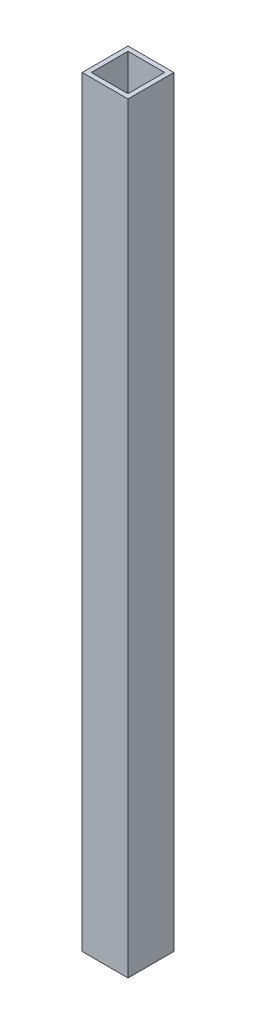
SolidWorks part; units mm, degrees
material "氧化铝"
ref_plane "前视基准面" through (0, 0, 0) normal (0, 0, 1) x (1, 0, 0)
ref_plane "上视基准面" through (0, 0, 0) normal (0, 1, 0) x (1, 0, 0)
ref_plane "右视基准面" through (0, 0, 0) normal (1, 0, 0) x (0, 0, -1)
other "Configuration Table"
sketch "草图1" plane through (0, 0, 0) normal (0, 1, 0) x (1, 0, 0)
  line L1 (-4, -4) -> (4, -4)
  line L2 (-4, -4) -> (-4, 4)
  line L3 (-4, 4) -> (4, 4)
  line L4 (4, -4) -> (4, 4)
  line L5 (-4, -4) -> (4, 4) construction
  line L6 (-4, 4) -> (4, -4) construction
  line L7 (-5, 5) -> (5, 5)
  line L8 (-5, 5) -> (-5, -5)
  line L9 (-5, -5) -> (5, -5)
  line L10 (5, 5) -> (5, -5)
  line L11 (-5, 5) -> (5, -5) construction
  line L12 (-5, -5) -> (5, 5) construction
  point P0 (0, 0)
  point P6 (0, 0)
  dimension "D1" = 1
  dimension "D2" = 10
  dimension "D3" = 10
  dimension "D4" = 1
extrude "凸台-拉伸1" add sketch "草图1" along normal blind 166
